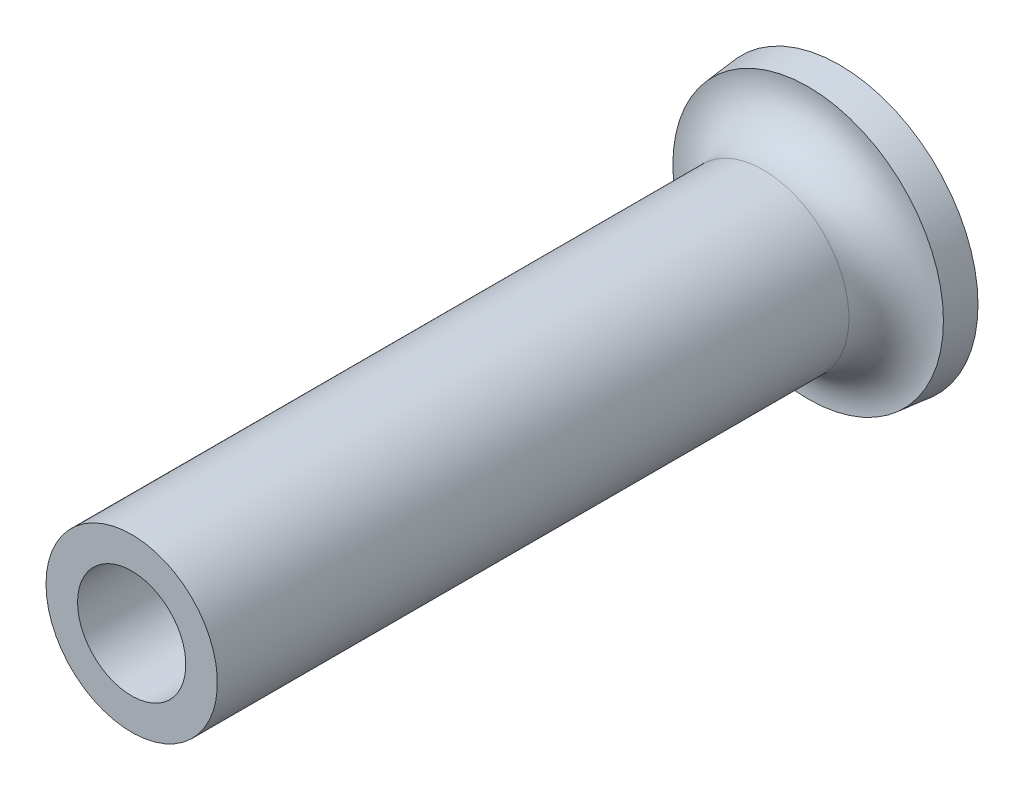
SolidWorks part; units mm, degrees
material "AISI Type 316L stainless steel"
ref_plane "Front Plane" through (0, 0, 0) normal (0, 0, 1) x (1, 0, 0)
ref_plane "Top Plane" through (0, 0, 0) normal (0, 1, 0) x (1, 0, 0)
ref_plane "Right Plane" through (0, 0, 0) normal (1, 0, 0) x (0, 0, -1)
sketch "Sketch1" plane through (0, 0, 0) normal (1, 0, 0) x (0, 0, -1)
  line L0 (0, 0) -> (-37.4423, 0) construction
  line L1 (0, 1.9) -> (-14.005, 1.9)
  arc A0 (0, 1.9) -> (0.995, 3) centre (0, 2.9) ccw
  dimension "D3" = 1
  dimension "D1" = 3.8
  dimension "D2" = 6
  dimension "D4" = 15
revolve "Revolve-Thin1" add sketch "Sketch1" angle 360 about L0 wall 0.7
